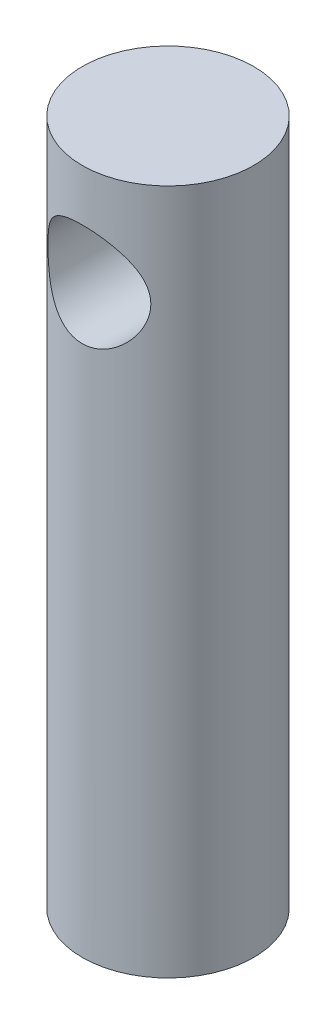
SolidWorks part; units mm, degrees
ref_plane "前视基准面" through (0, 0, 0) normal (0, 0, 1) x (1, 0, 0)
ref_plane "上视基准面" through (0, 0, 0) normal (0, 1, 0) x (1, 0, 0)
ref_plane "右视基准面" through (0, 0, 0) normal (1, 0, 0) x (0, 0, -1)
sketch "草图1" plane through (0, 0, 0) normal (0, 1, 0) x (1, 0, 0)
  circle A0 centre (0, 0) radius 125
  dimension "D1" = 250
extrude "凸台-拉伸1" add sketch "草图1" along normal blind 1000
sketch "草图3" plane through (0, 0, 0) normal (0, 0, 1) x (1, 0, 0)
  line L0 (-133.4177, 1000) -> (-17.664, 1000) construction
  line L3 (125, 1000) -> (-125, 1000) construction
  line L4 (0, 1000) -> (0, 850) construction
  circle A0 centre (0, 850) radius 75
  dimension "D2" = 150
  dimension "D1" = 150
extrude "切除-拉伸1" cut sketch "草图3" against normal through all both and the other way through all
